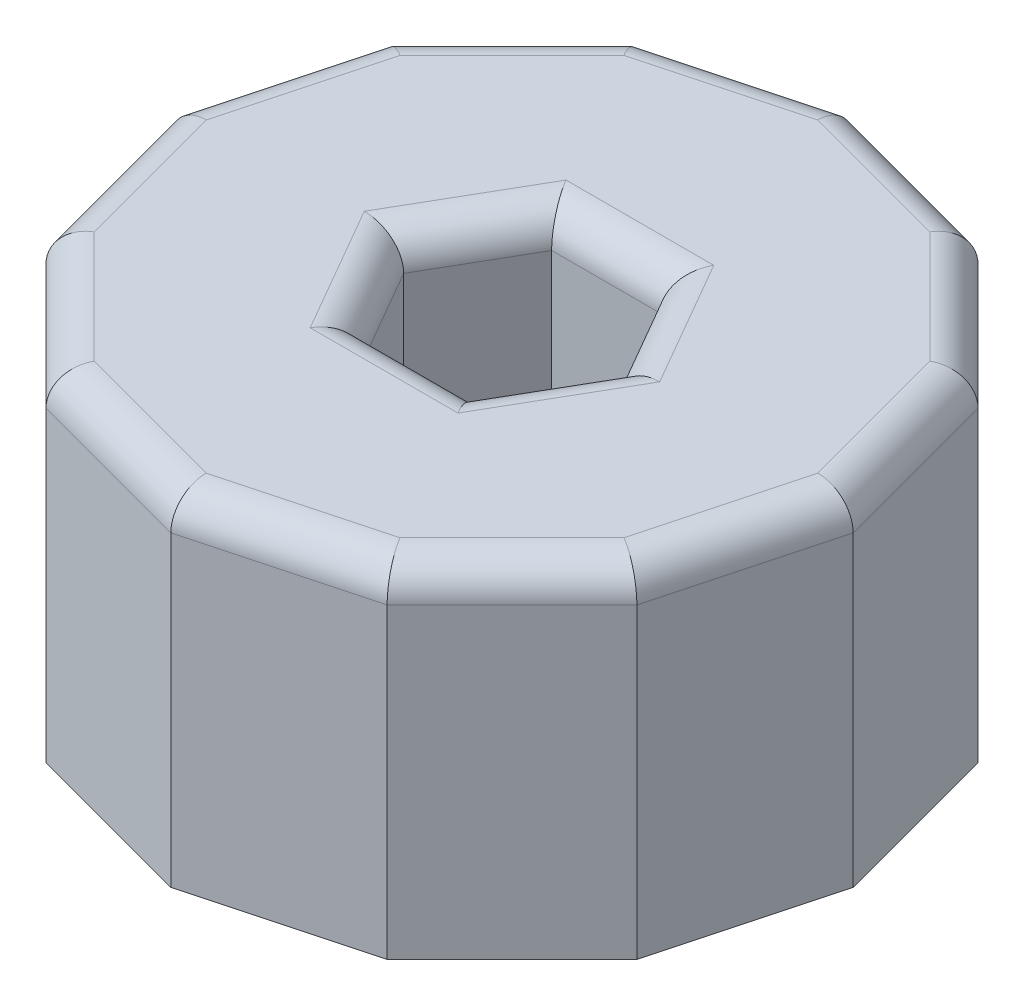
SolidWorks part; units mm, degrees
ref_plane "Front Plane" through (0, 0, 0) normal (0, 0, 1) x (1, 0, 0)
ref_plane "Top Plane" through (0, 0, 0) normal (0, 1, 0) x (1, 0, 0)
ref_plane "Right Plane" through (0, 0, 0) normal (1, 0, 0) x (0, 0, -1)
sketch "Sketch1" plane through (0, 0, 0) normal (0, 1, 0) x (1, 0, 0)
  line L0 (-10, 0) -> (-8.6603, -5)
  line L1 (10, 0) -> (8.6603, 5)
  line L2 (8.6603, 5) -> (5, 8.6603)
  line L3 (5, 8.6603) -> (0, 10)
  line L4 (0, 10) -> (-5, 8.6603)
  line L5 (-5, 8.6603) -> (-8.6603, 5)
  line L6 (-8.6603, 5) -> (-10, 0)
  line L7 (-8.6603, -5) -> (-5, -8.6603)
  line L8 (-5, -8.6603) -> (0, -10)
  line L9 (0, -10) -> (5, -8.6603)
  line L10 (5, -8.6603) -> (8.6603, -5)
  line L11 (8.6603, -5) -> (10, 0)
  circle A1 centre (0, 0) radius 10 construction
  circle A2 centre (0, 0) radius 1.6
extrude "Boss-Extrude1" add sketch "Sketch1" along normal blind 10
sketch "Sketch2" plane through (0, 10, 0) normal (0, 1, 0) x (1, 0, 0)
  line L1 (3.1754, 0) -> (1.5877, 2.75)
  line L2 (1.5877, 2.75) -> (-1.5877, 2.75)
  line L3 (-1.5877, 2.75) -> (-3.1754, 0)
  line L4 (-3.1754, 0) -> (-1.5877, -2.75)
  line L5 (-1.5877, -2.75) -> (1.5877, -2.75)
  line L6 (1.5877, -2.75) -> (3.1754, 0)
  circle A0 centre (0, 0) radius 2.75 construction
  dimension "D1" = 5.5
extrude "Cut-Extrude1" cut sketch "Sketch2" against normal blind 5
fillet "Fillet1" radius 1 18 edges at (2.5, 10, 9.3301) (-2.5, 10, 9.3301) (-6.8301, 10, 6.8301) (-9.3301, 10, 2.5) (-9.3301, 10, -2.5) (-6.8301, 10, -6.8301) (-2.5, 10, -9.3301) (2.5, 10, -9.3301) (6.8301, 10, -6.8301) (9.3301, 10, -2.5) (9.3301, 10, 2.5) (6.8301, 10, 6.8301) (2.3816, 10, -1.375) (0, 10, -2.75) (-2.3816, 10, -1.375) (-2.3816, 10, 1.375) (0, 10, 2.75) (2.3816, 10, 1.375)
